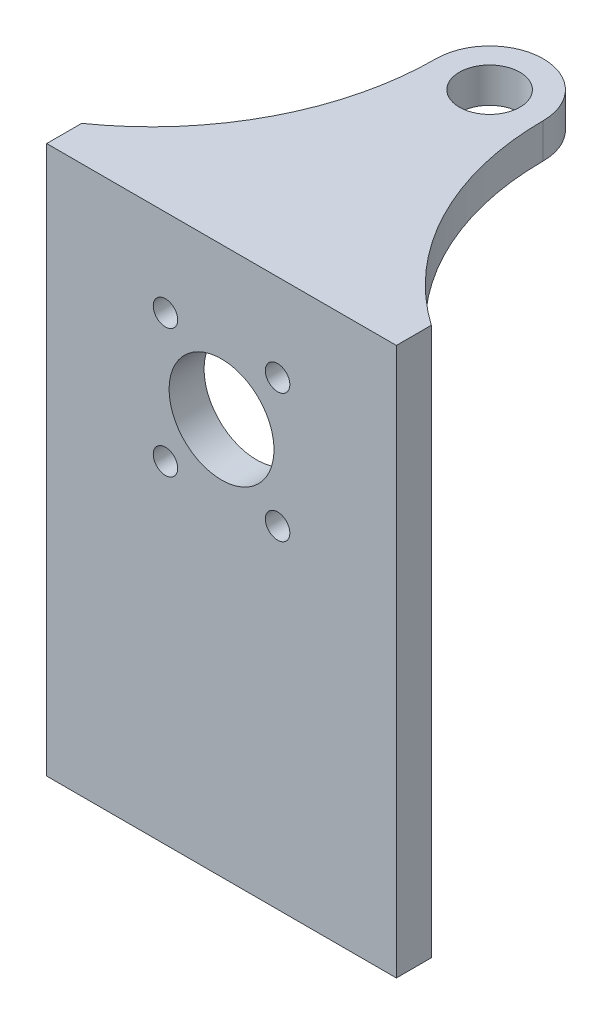
SolidWorks part; units mm, degrees
material "ABS"
ref_plane "Front Plane" through (0, 0, 0) normal (0, 0, 1) x (1, 0, 0)
ref_plane "Top Plane" through (0, 0, 0) normal (0, 1, 0) x (1, 0, 0)
ref_plane "Right Plane" through (0, 0, 0) normal (1, 0, 0) x (0, 0, -1)
sketch "Sketch1" plane through (0, 0, 0) normal (0, 1, 0) x (1, 0, 0)
  line L0 (-57.1637, 16.1905) -> (-57.1637, -8.4095) construction
  line L1 (-72.1637, 16.1905) -> (-42.1637, 16.1905)
  line L2 (-72.1637, 16.1905) -> (-72.1637, -8.4095)
  line L3 (-72.1637, -8.4095) -> (-42.1637, -8.4095)
  line L4 (-42.1637, 16.1905) -> (-42.1637, -8.4095)
  circle A0 centre (-57.1637, 11.5905) radius 2.6
  circle A1 centre (-57.1637, 11.5905) radius 4.6
  arc A2 (-61.7637, 11.5905) -> (-72.1637, -8.4095) centre (-86.1944, 11.5905) cw
  arc A3 (-52.5637, 11.5905) -> (-42.1637, -8.4095) centre (-28.1329, 11.5905) ccw
  point P8 (-57.1637, 14.1905)
  dimension "D4" = 5.2
  dimension "D1" = 30
  dimension "D2" = 20
  dimension "D3" = 2
extrude "Boss-Extrude1" add sketch "Sketch1" against normal blind 3 contours A1 L0 A0 | L0 A1 A0 | A1 L0 L3 A3 | L0 A1 A2 L3
sketch "Sketch2" plane through (0, -3, 0) normal (0, -1, 0) x (-1, 0, 0)
  line L1 (42.1637, -11.4095) -> (72.1637, -11.4095)
  line L2 (42.1637, -11.4095) -> (42.1637, -8.4095)
  line L3 (42.1637, -8.4095) -> (72.1637, -8.4095)
  line L4 (72.1637, -11.4095) -> (72.1637, -8.4095)
  line L5 (72.1637, -8.4095) -> (42.1637, -8.4095) construction
  dimension "D1" = 3
extrude "Boss-Extrude2" add sketch "Sketch2" along normal blind 44 and the other way up to surface contours L1 L4 L3 L2 other way up to face at (-57.1637, 0, -2.1049)
sketch "Sketch3" plane through (0, -47, 0) normal (0, -1, 0) x (-1, 0, 0)
  line L0 (57.1637, -8.4095) -> (57.1637, -13.8095) construction
  line L3 (42.1637, -9.9095) -> (72.1637, -9.9095) construction
  line L6 (42.1637, -8.4095) -> (72.1637, -8.4095) construction
  line L8 (72.1637, -11.4095) -> (72.1637, -8.4095) construction
  circle A0 centre (47.1637, -9.9095) radius 1
  circle A1 centre (67.1637, -9.9095) radius 1
  dimension "D2" = 2
  dimension "D1" = 20
extrude "Cut-Extrude1" cut sketch "Sketch3" against normal blind 10 contours A0 | A1
sketch "Sketch5" plane through (0, 0, 8.4095) normal (0, 0, -1) x (-1, 0, 0)
  line L0 (57.1637, -3) -> (57.1637, -47) construction
  line L1 (72.1637, -3) -> (42.1637, -3) construction
  line L2 (42.1637, -47) -> (72.1637, -47) construction
  line L3 (42.1637, -13) -> (72.1637, -13) construction
  line L7 (52.3537, -18.515) -> (61.9737, -18.515) construction
  line L8 (52.3537, -18.515) -> (52.3537, -7.485) construction
  line L9 (52.3537, -7.485) -> (61.9737, -7.485) construction
  line L10 (61.9737, -18.515) -> (61.9737, -7.485) construction
  line L11 (52.3537, -18.515) -> (61.9737, -7.485) construction
  line L12 (52.3537, -7.485) -> (61.9737, -18.515) construction
  circle A0 centre (57.1637, -13) radius 4.5
  circle A1 centre (52.3537, -7.485) radius 1.05
  circle A2 centre (52.3537, -18.515) radius 1.05
  circle A3 centre (61.9737, -7.485) radius 1.05
  circle A4 centre (61.9737, -18.515) radius 1.05
  dimension "D1" = 9
  dimension "D2" = 2.1
  dimension "D3" = 9.62
  dimension "D4" = 11.03
  dimension "D5" = 10
extrude "Cut-Extrude2" cut sketch "Sketch5" against normal through all
